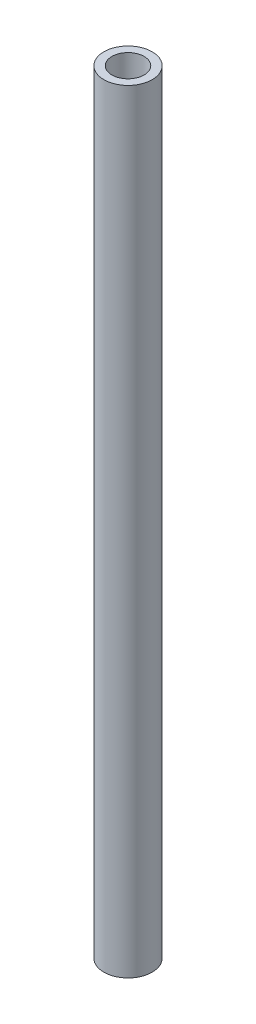
SolidWorks part; units mm, degrees
material "Plain Carbon Steel"
ref_plane "Front Plane" through (0, 0, 0) normal (0, 0, 1) x (1, 0, 0)
ref_plane "Top Plane" through (0, 0, 0) normal (0, 1, 0) x (1, 0, 0)
ref_plane "Right Plane" through (0, 0, 0) normal (1, 0, 0) x (0, 0, -1)
sketch "Sketch1" plane through (0, 0, 0) normal (0, 1, 0) x (1, 0, 0)
  circle A0 centre (0, 0) radius 9.525
  circle A1 centre (0, 0) radius 6.35
  dimension "D1" = 19.05
  dimension "D2" = 3.175
extrude "Boss-Extrude1" add sketch "Sketch1" along normal blind 304.8
